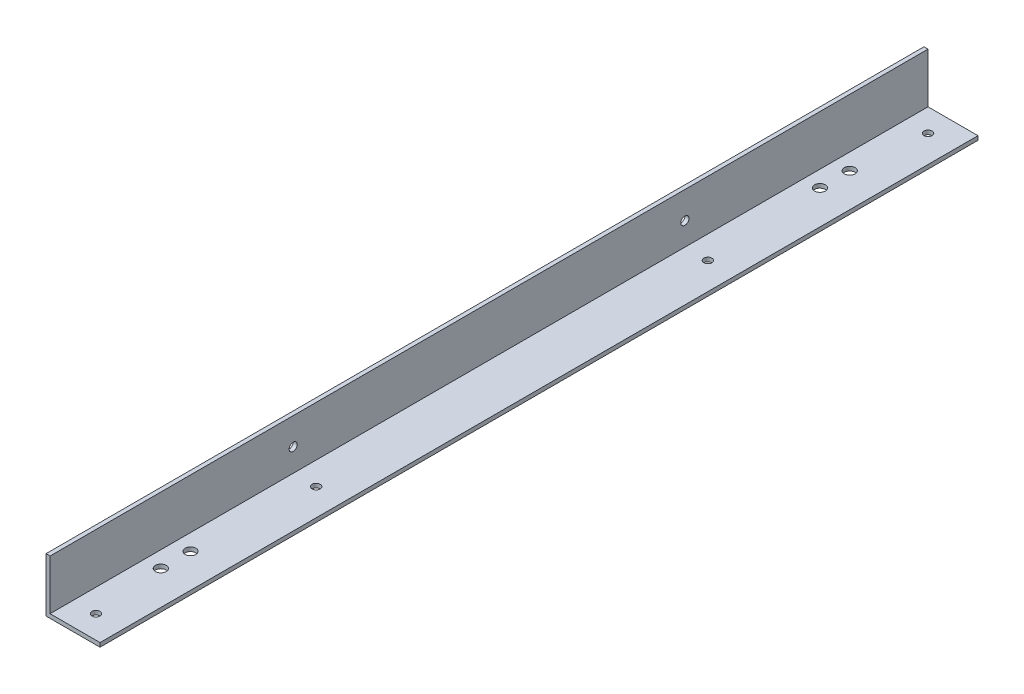
SolidWorks part; units mm, degrees
ref_plane "Plan de face" through (0, 0, 0) normal (0, 0, 1) x (1, 0, 0)
ref_plane "Plan de dessus" through (0, 0, 0) normal (0, 1, 0) x (1, 0, 0)
ref_plane "Plan de droite" through (0, 0, 0) normal (1, 0, 0) x (0, 0, -1)
sketch "Esquisse1" plane through (0, 0, 0) normal (0, 0, 1) x (1, 0, 0)
  line L0 (-17.4317, 4.7734) -> (-17.4317, -15.2266)
  line L1 (-17.4317, -15.2266) -> (2.5683, -15.2266)
  line L2 (2.5683, -15.2266) -> (2.5683, -13.7266)
  line L3 (2.5683, -13.7266) -> (-15.9317, -13.7266)
  line L4 (-15.9317, -13.7266) -> (-15.9317, 4.7734)
  line L5 (-15.9317, 4.7734) -> (-17.4317, 4.7734)
  dimension "D1" = 1.5
  dimension "D2" = 1.5
  dimension "D3" = 20
  dimension "D4" = 20
extrude "Extrusion1" add sketch "Esquisse1" along normal blind 325
sketch "Esquisse2" plane through (0, -13.7266, 0) normal (0, 1, 0) x (-1, 0, 0)
  line L0 (-2.5683, 325) -> (-2.5683, 0) construction
  line L1 (-2.5683, 325) -> (15.9317, 325) construction
  line L2 (-2.5683, 0) -> (15.9317, 0) construction
  line L3 (9.9317, 290) -> (9.9317, 279) construction
  line L4 (9.9317, 46) -> (9.9317, 35) construction
  line L5 (17.4317, 325) -> (-2.5683, 325) construction
  line L6 (15.9317, 325) -> (15.9317, 0) construction
  circle A0 centre (7.4317, 8.5) radius 1.5
  circle A1 centre (7.4317, 316.5) radius 1.5
  circle A2 centre (9.9317, 35) radius 2
  circle A3 centre (9.9317, 46) radius 2
  circle A4 centre (9.9317, 290) radius 2
  circle A5 centre (9.9317, 279) radius 2
  circle A6 centre (7.4317, 235) radius 1.5
  circle A7 centre (7.4317, 90) radius 1.5
  point P22 (7.4317, 325)
  dimension "D1" = 8.5
  dimension "D5" = 11
  dimension "D7" = 11
  dimension "D11" = 90
  dimension "D2" = 8.5
  dimension "D3" = 10
  dimension "D4" = 10
  dimension "D6" = 35
  dimension "D8" = 35
  dimension "D9" = 6
  dimension "D10" = 6
  dimension "D12" = 90
  dimension "D13" = 10
  dimension "D14" = 10
extrude "Extrusion2" cut sketch "Esquisse2" against normal blind 300
sketch "Esquisse3" plane through (-17.4317, 0, 0) normal (-1, 0, 0) x (0, 0, 1)
  line L0 (325, 4.7734) -> (325, -15.2266) construction
  line L1 (325, -15.2266) -> (0, -15.2266) construction
  line L2 (0, 4.7734) -> (0, -15.2266) construction
  circle A0 centre (235, -5.2266) radius 1.5
  circle A1 centre (90, -5.2266) radius 1.5
  dimension "D1" = 90
  dimension "D3" = 90
  dimension "D2" = 10
extrude "Extrusion3" cut sketch "Esquisse3" against normal blind 10
